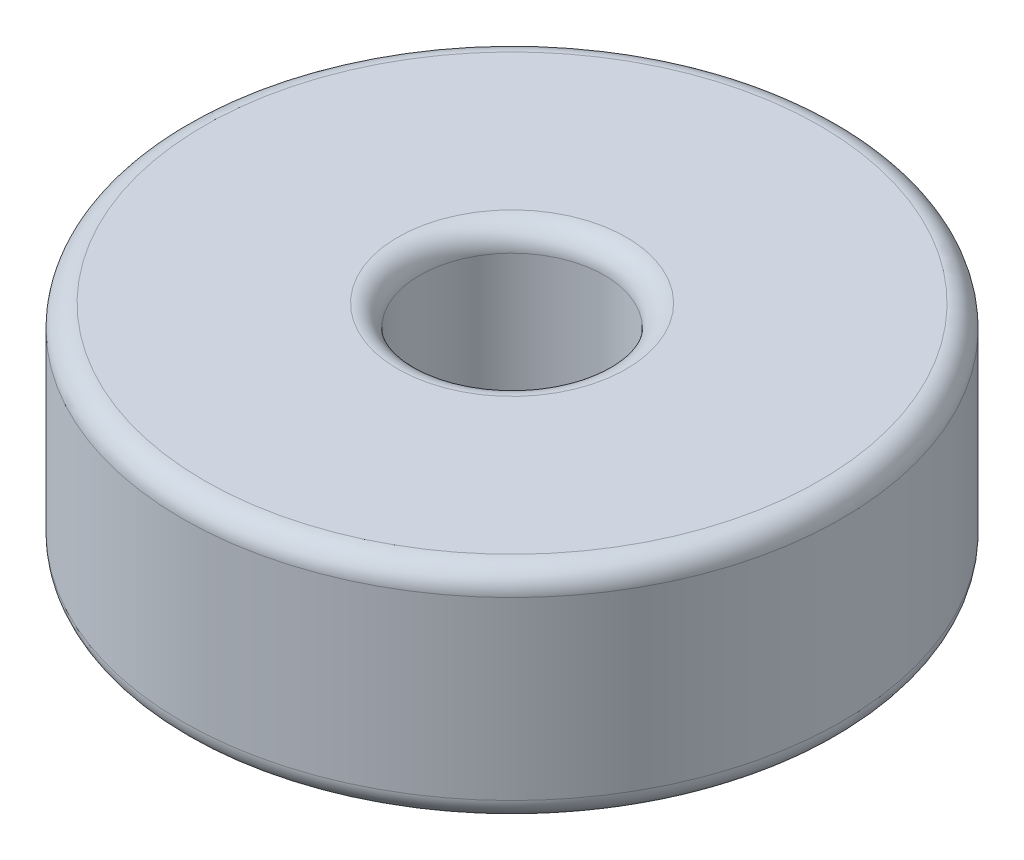
SolidWorks part; units mm, degrees
ref_plane "Front Plane" through (0, 0, 0) normal (0, 0, 1) x (1, 0, 0)
ref_plane "Top Plane" through (0, 0, 0) normal (0, 1, 0) x (1, 0, 0)
ref_plane "Right Plane" through (0, 0, 0) normal (1, 0, 0) x (0, 0, -1)
sketch "Sketch1" plane through (0, 0, 0) normal (0, 1, 0) x (1, 0, 0)
  circle A0 centre (0, 0) radius 2.1
  circle A1 centre (0, 0) radius 7.5
  dimension "D1" = 4.2
  dimension "D2" = 15
extrude "Boss-Extrude1" add sketch "Sketch1" along normal blind 5
fillet "Fillet1" radius 0.5 4 edges at (0, 0, 2.1) (0, 5, 2.1) (0, 0, 7.5) (0, 5, 7.5)
